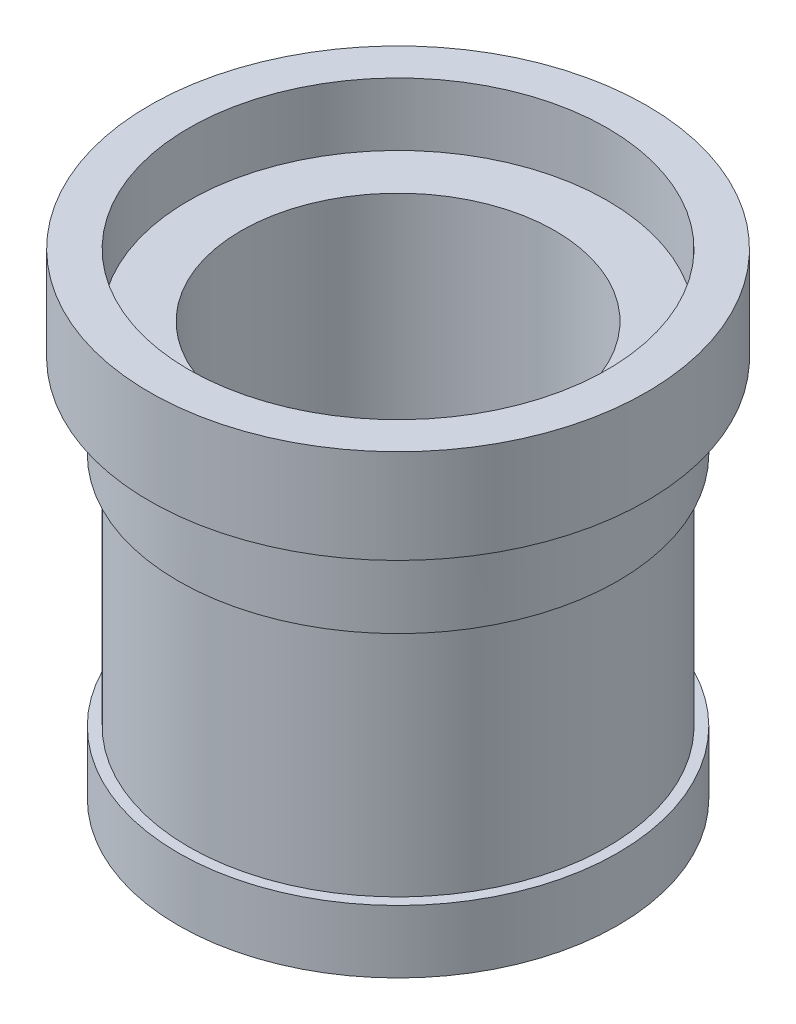
SolidWorks part; units mm, degrees
ref_plane "Front Plane" through (0, 0, 0) normal (0, 0, 1) x (1, 0, 0)
ref_plane "Top Plane" through (0, 0, 0) normal (0, 1, 0) x (1, 0, 0)
ref_plane "Right Plane" through (0, 0, 0) normal (1, 0, 0) x (0, 0, -1)
sketch "Sketch1" plane through (0, 0, 0) normal (0, 0, 1) x (1, 0, 0)
  line L0 (0, -44.5043) -> (0, 56.7374) construction
  line L1 (30, -27.8557) -> (30, 51.1443)
  line L2 (42, -27.8557) -> (42, -15.8557)
  line L3 (42, -27.8557) -> (30, -27.8557)
  line L4 (40, -15.8557) -> (40, 29.1443)
  line L5 (42, -15.8557) -> (40, -15.8557)
  line L6 (42, 29.1443) -> (42, 45.1443)
  line L7 (40, 29.1443) -> (42, 29.1443)
  line L8 (47.5, 45.1443) -> (47.5, 63.1443)
  line L9 (42, 45.1443) -> (47.5, 45.1443)
  line L10 (40, 63.1443) -> (40, 51.1443)
  line L11 (40, 63.1443) -> (47.5, 63.1443)
  line L12 (40, 51.1443) -> (30, 51.1443)
  dimension "D1" = 12
  dimension "D2" = 45
  dimension "D3" = 16
  dimension "D4" = 18
  dimension "D5" = 12
  dimension "D6" = 42
  dimension "D7" = 40
  dimension "D8" = 42
  dimension "D9" = 47.5
  dimension "D10" = 40
  dimension "D11" = 30
revolve "Revolve1" add sketch "Sketch1" angle 360 about L0
sketch "Sketch2" plane through (0, 0, 0) normal (0, 0, 1) x (1, 0, 0)
  line L0 (-42, 45.1443) -> (42, 45.1443) construction
  line L1 (-42, 45.1443) -> (-39, 45.1443)
  line L2 (-42, 45.1443) -> (-42, 35.1443)
  line L3 (-42, 35.1443) -> (-39, 35.1443)
  line L4 (-39, 45.1443) -> (-39, 35.1443)
  line L5 (-47.5, 45.1443) -> (47.5, 45.1443) construction
  line L7 (-42, 29.1443) -> (42, 29.1443) construction
  point P10 (0, 0)
  dimension "D1" = 6
  dimension "D2" = 3
  dimension "D3" = 10
extrude "Cut-Extrude3" cut sketch "Sketch2" against normal mid plane 10
